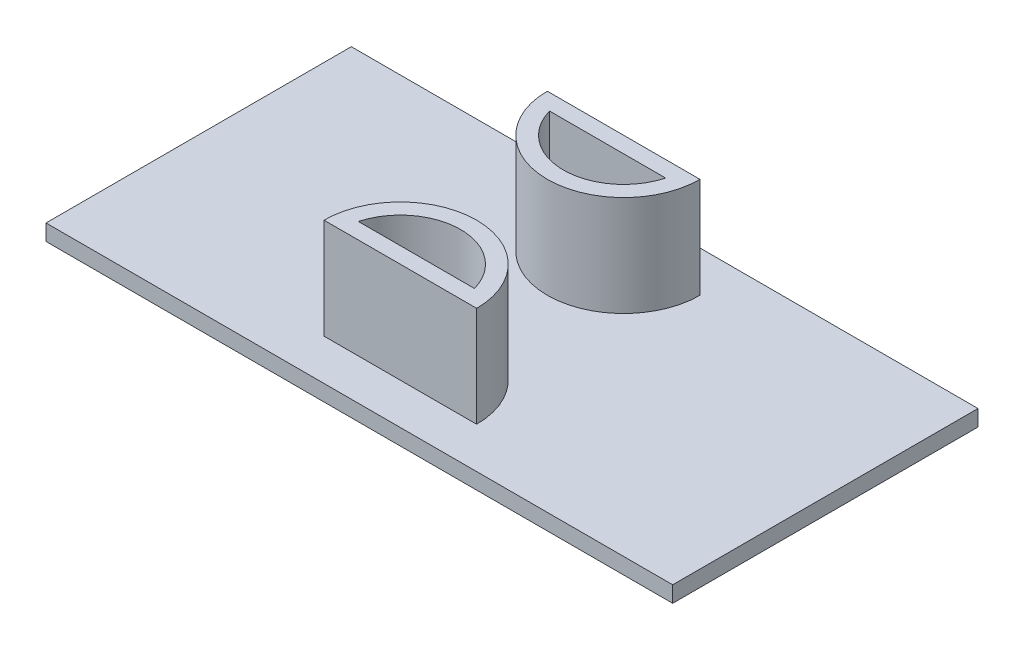
SolidWorks part; units mm, degrees
ref_plane "Front Plane" through (0, 0, 0) normal (0, 0, 1) x (1, 0, 0)
ref_plane "Top Plane" through (0, 0, 0) normal (0, 1, 0) x (1, 0, 0)
ref_plane "Right Plane" through (0, 0, 0) normal (1, 0, 0) x (0, 0, -1)
sketch "Sketch1" plane through (0, 0, 0) normal (0, 1, 0) x (1, 0, 0)
  line L1 (-12.4184, 10.2118) -> (26.5816, 10.2118)
  line L2 (-12.4184, 10.2118) -> (-12.4184, -8.7882)
  line L3 (-12.4184, -8.7882) -> (26.5816, -8.7882)
  line L4 (26.5816, 10.2118) -> (26.5816, -8.7882)
  dimension "D1" = 39
  dimension "D2" = 19
extrude "Boss-Extrude1" add sketch "Sketch1" along normal blind 1
sketch "Sketch2" plane through (0, 1, 0) normal (0, 1, 0) x (1, 0, 0)
  line L0 (7.0816, 10.2118) -> (7.0816, -8.7882) construction
  line L1 (26.5816, 10.2118) -> (-12.4184, 10.2118) construction
  line L2 (-12.4184, -8.7882) -> (26.5816, -8.7882) construction
  line L3 (-12.4184, 0.7118) -> (26.5816, 0.7118) construction
  line L4 (-12.4184, 10.2118) -> (-12.4184, -8.7882) construction
  line L5 (26.5816, -8.7882) -> (26.5816, 10.2118) construction
  line L6 (2.3316, 7.6618) -> (11.8316, 7.6618)
  line L7 (3.4674, 6.6618) -> (10.6958, 6.6618)
  line L8 (3.4674, -5.2382) -> (10.6958, -5.2382)
  line L9 (2.3316, -6.2382) -> (11.8316, -6.2382)
  arc A0 (2.3316, 7.6618) -> (11.8316, 7.6618) centre (7.0816, 7.6618) ccw
  arc A1 (3.4674, 6.6618) -> (10.6958, 6.6618) centre (7.0816, 7.6618) ccw
  arc A2 (3.4674, -5.2382) -> (10.6958, -5.2382) centre (7.0816, -6.2382) cw
  arc A3 (2.3316, -6.2382) -> (11.8316, -6.2382) centre (7.0816, -6.2382) cw
  point P12 (7.0816, 0.7118)
  dimension "D1" = 9.5
  dimension "D2" = 6.95
  dimension "D3" = 1
extrude "Boss-Extrude2" add sketch "Sketch2" along normal blind 6.25
